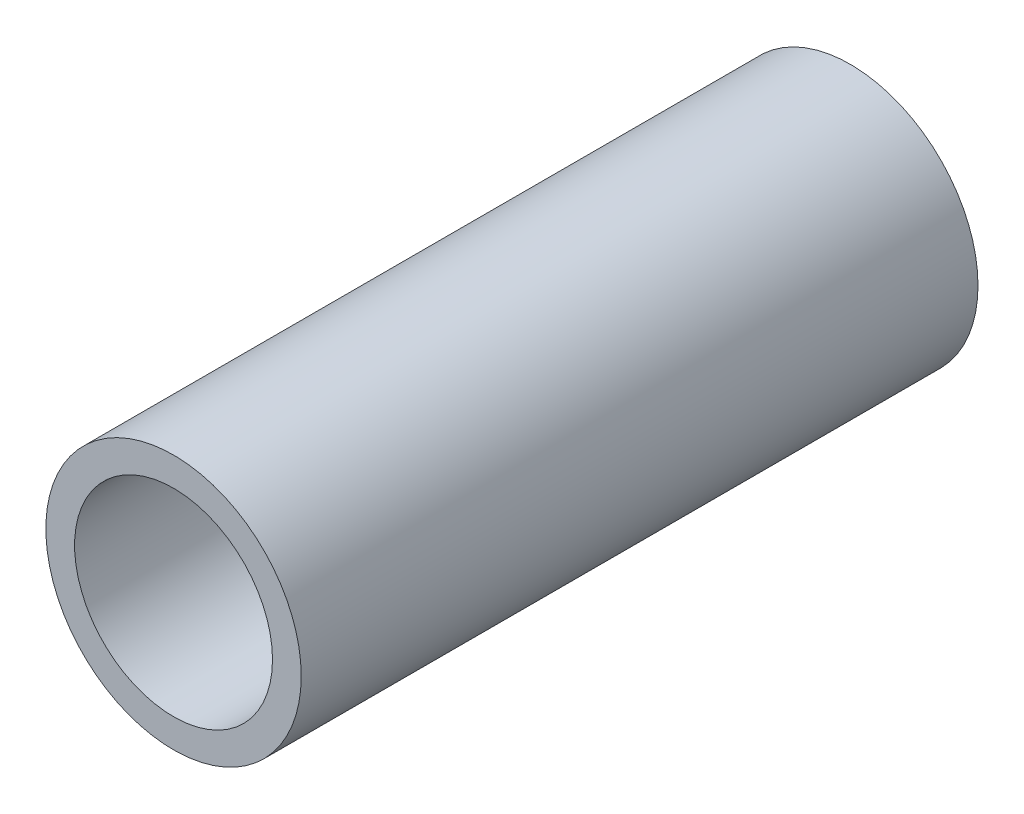
SolidWorks part; units mm, degrees
ref_plane "Спереди" through (0, 0, 0) normal (0, 0, 1) x (1, 0, 0)
ref_plane "Сверху" through (0, 0, 0) normal (0, 1, 0) x (1, 0, 0)
ref_plane "Справа" through (0, 0, 0) normal (1, 0, 0) x (0, 0, -1)
sketch "Эскиз1" plane through (0, 0, 0) normal (0, 0, 1) x (1, 0, 0)
  circle A0 centre (0, 0) radius 1
  circle A1 centre (0, 0) radius 0.775
extrude "Бобышка-Вытянуть1" add sketch "Эскиз1" along normal blind 5.3
